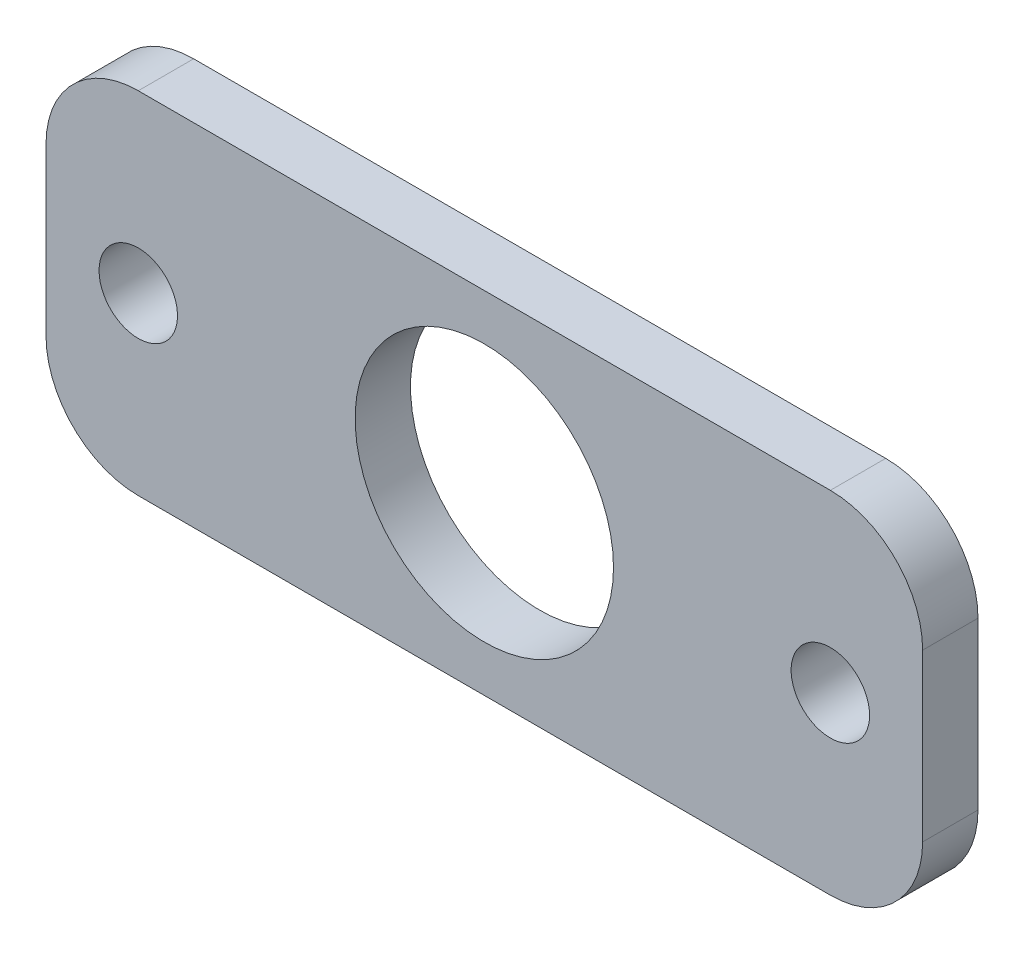
SolidWorks part; units mm, degrees
material "Plain Carbon Steel"
ref_plane "Front Plane" through (0, 0, 0) normal (0, 0, 1) x (1, 0, 0)
ref_plane "Top Plane" through (0, 0, 0) normal (0, 1, 0) x (1, 0, 0)
ref_plane "Right Plane" through (0, 0, 0) normal (1, 0, 0) x (0, 0, -1)
sketch "Sketch1" plane through (0, 0, 0) normal (0, 0, 1) x (1, 0, 0)
  line L0 (-424, 0) -> (424, 0) construction
  line L1 (399, 0) -> (304, 0)
  line L2 (399, 0) -> (399, -38)
  line L3 (399, -38) -> (304, -38)
  line L4 (304, 0) -> (304, -38)
  line L5 (429, -38) -> (-429, -38) construction
  line L6 (351.5, -19) -> (399, -19) construction
  line L7 (351.5, -19) -> (351.5, -38) construction
  line L10 (304, -19) -> (351.5, -19) construction
  line L12 (399, 3) -> (304, 3) construction
  line L13 (399, 0) -> (399, 6) construction
  line L14 (304, 0) -> (304, 6) construction
  line L15 (351.5, 3) -> (351.5, -90.1001) construction
  circle A0 centre (351.5, -19) radius 14
  circle A3 centre (389, -19) radius 4.25
  circle A4 centre (314, -19) radius 4.25
  dimension "D1" = 28
  dimension "D2" = 8.5
  dimension "D4" = 95
  dimension "D3" = 10
extrude "Boss-Extrude1" add sketch "Sketch1" along normal blind 6
fillet "Fillet1" radius 10 4 edges at (399, 0, 3) (399, -38, 3) (304, -38, 3) (304, 0, 3)
